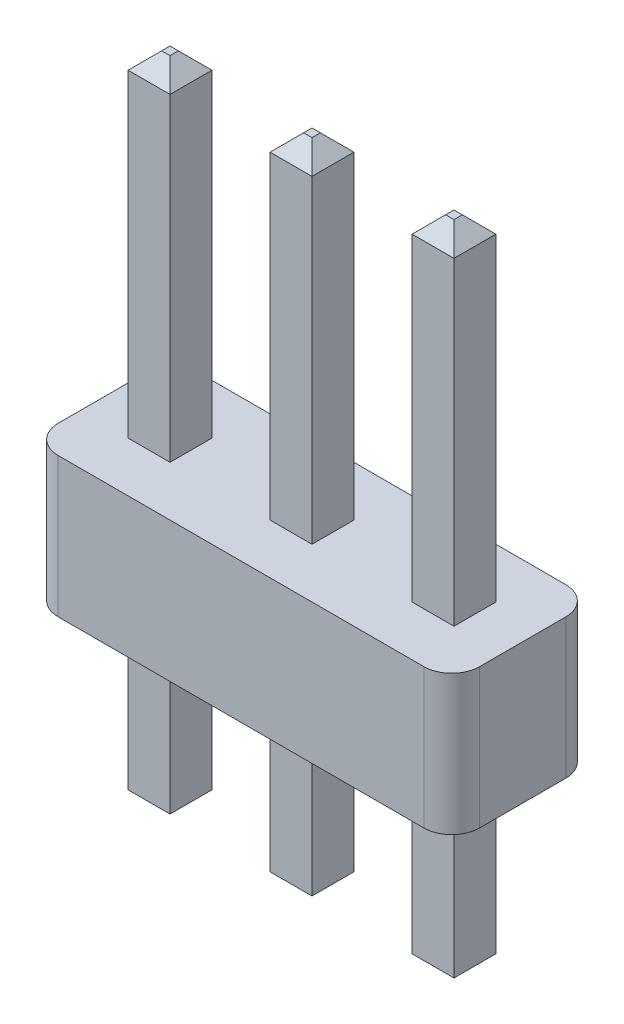
SolidWorks part; units mm, degrees
ref_plane "Front Plane" through (0, 0, 0) normal (0, 0, 1) x (1, 0, 0)
ref_plane "Top Plane" through (0, 0, 0) normal (0, 1, 0) x (1, 0, 0)
ref_plane "Right Plane" through (0, 0, 0) normal (1, 0, 0) x (0, 0, -1)
ref_plane "Plane1" through (0, 0, 0) normal (0, 1, 0) x (-1, 0, 0)
sketch "Sketch1" plane through (0, 0, 0) normal (0, 1, 0) x (-1, 0, 0)
  line L0 (-3.27, 1.27) -> (3.27, 1.27)
  line L1 (3.77, 0.77) -> (3.77, -0.77)
  line L2 (3.27, -1.27) -> (-3.27, -1.27)
  line L3 (-3.77, -0.77) -> (-3.77, 0.77)
  line L4 (0, 55) -> (0, -55) construction
  line L5 (55, 0) -> (-55, 0) construction
  arc A0 (3.77, 0.77) -> (3.27, 1.27) centre (3.27, 0.77) ccw
  arc A1 (3.27, -1.27) -> (3.77, -0.77) centre (3.27, -0.77) ccw
  arc A2 (-3.77, -0.77) -> (-3.27, -1.27) centre (-3.27, -0.77) ccw
  arc A3 (-3.27, 1.27) -> (-3.77, 0.77) centre (-3.27, 0.77) ccw
  dimension "D5" = 0.5
  dimension "D1" = 7.54
  dimension "D2" = 2.54
  dimension "D3" = 3.77
  dimension "D4" = 1.27
extrude "Boss-Extrude1" add sketch "Sketch1" along normal blind 2.5
ref_plane "Plane2" through (0, 0, 0) normal (0, 1, 0) x (-1, 0, 0)
sketch "Sketch2" plane through (0, 0, 0) normal (0, 1, 0) x (-1, 0, 0)
  line L0 (2.165, 0.375) -> (2.915, 0.375)
  line L1 (2.915, 0.375) -> (2.915, -0.375)
  line L2 (2.915, -0.375) -> (2.165, -0.375)
  line L3 (2.165, -0.375) -> (2.165, 0.375)
  line L4 (0.375, -0.375) -> (-0.375, -0.375)
  line L5 (-0.375, -0.375) -> (-0.375, 0.375)
  line L6 (-0.375, 0.375) -> (0.375, 0.375)
  line L7 (0.375, 0.375) -> (0.375, -0.375)
  line L8 (-0.375, 0.375) -> (0.375, -0.375) construction
  line L9 (2.165, -0.375) -> (2.915, 0.375) construction
  line L10 (55, 0) -> (-55, 0) construction
  line L13 (-2.915, -0.375) -> (-2.165, -0.375)
  line L14 (-2.915, -0.375) -> (-2.915, 0.375)
  line L15 (-2.915, 0.375) -> (-2.165, 0.375)
  line L16 (-2.165, -0.375) -> (-2.165, 0.375)
  line L17 (-2.915, -0.375) -> (-2.165, 0.375) construction
  line L18 (-2.915, 0.375) -> (-2.165, -0.375) construction
  line L19 (3.77, -0.77) -> (3.77, 0.77) construction
  point P8 (0, 0)
  point P9 (2.54, 0)
  point P14 (-2.54, 0)
  dimension "D1" = 2.54
  dimension "D2" = 0.75
  dimension "D3" = 0.855
  dimension "D4" = 2.54
  dimension "D5" = 0.75
  dimension "D6" = 0.75
extrude "Boss-Extrude2" add sketch "Sketch2" along normal blind 8.5 and the other way blind 3.25
chamfer "Chamfer1" distance 0.3 angle 45 24 edges at (-2.915, 8.5, 0) (-2.54, 8.5, -0.375) (-2.165, 8.5, 0) (-2.54, 8.5, 0.375) (-0.375, 8.5, 0) (0, 8.5, -0.375) (0.375, 8.5, 0) (0, 8.5, 0.375) (0, -3.25, -0.375) (0.375, -3.25, 0) (-0.375, -3.25, 0) (0, -3.25, 0.375) (-2.54, -3.25, 0.375) (-2.915, -3.25, 0) (-2.165, -3.25, 0) (-2.54, -3.25, -0.375) (2.54, -3.25, 0.375) (2.915, -3.25, 0) (2.54, -3.25, -0.375) (2.165, -3.25, 0) (2.54, 8.5, -0.375) (2.915, 8.5, 0) (2.54, 8.5, 0.375) (2.165, 8.5, 0)
